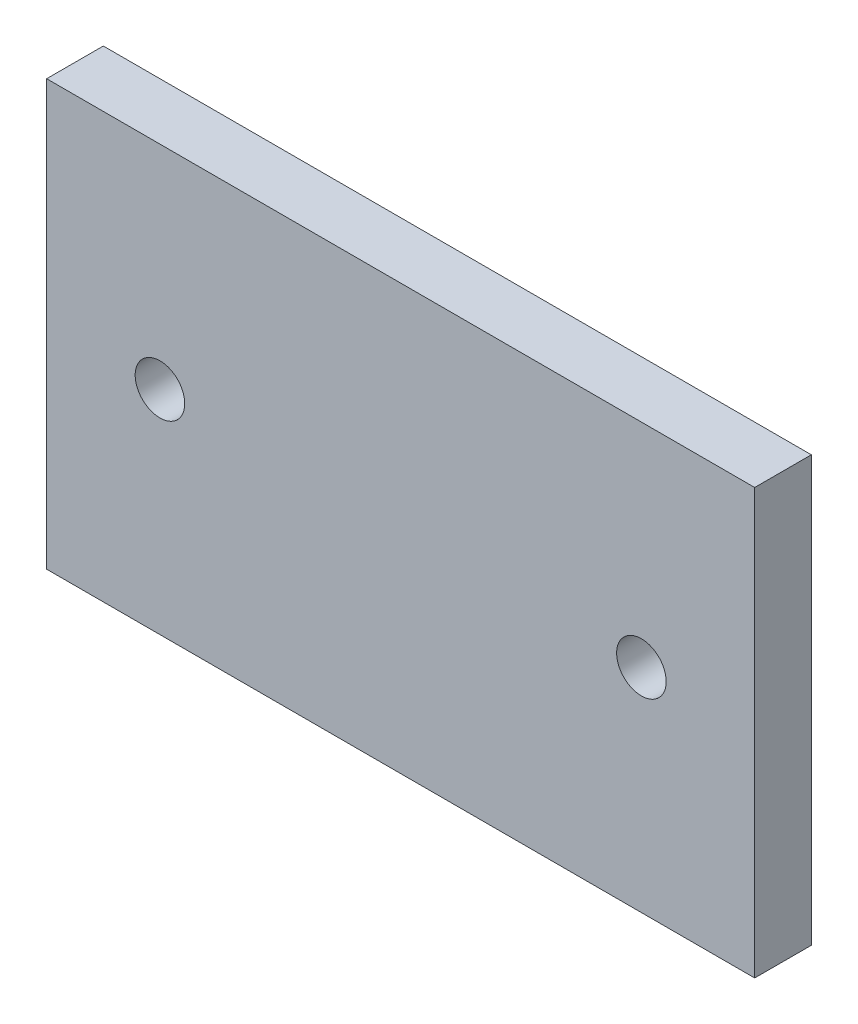
SolidWorks part; units mm, degrees
ref_plane "前视基准面" through (0, 0, 0) normal (0, 0, 1) x (1, 0, 0)
ref_plane "上视基准面" through (0, 0, 0) normal (0, 1, 0) x (1, 0, 0)
ref_plane "右视基准面" through (0, 0, 0) normal (1, 0, 0) x (0, 0, -1)
sketch "草图1" plane through (0, 0, 0) normal (0, 0, 1) x (1, 0, 0)
  line L1 (-100, 60) -> (100, 60)
  line L2 (-100, 60) -> (-100, -60)
  line L3 (-100, -60) -> (100, -60)
  line L4 (100, 60) -> (100, -60)
  line L5 (-100, 60) -> (100, -60) construction
  line L6 (-100, -60) -> (100, 60) construction
  point P0 (0, 0)
  dimension "D1" = 120
  dimension "D2" = 200
extrude "凸台-拉伸1" add sketch "草图1" along normal blind 16
sketch "草图2" plane through (0, 0, 16) normal (0, 0, 1) x (1, 0, 0)
  line L0 (-100, 0) -> (100, 0) construction
  line L1 (-100, 60) -> (-100, -60) construction
  line L2 (100, -60) -> (100, 60) construction
  line L3 (0, 0) -> (0, 60) construction
  line L4 (100, 60) -> (-100, 60) construction
  circle A0 centre (-68, 0) radius 7
  circle A1 centre (68, 0) radius 7
  dimension "D1" = 14
  dimension "D2" = 136
extrude "切除-拉伸1" cut sketch "草图2" against normal through all
